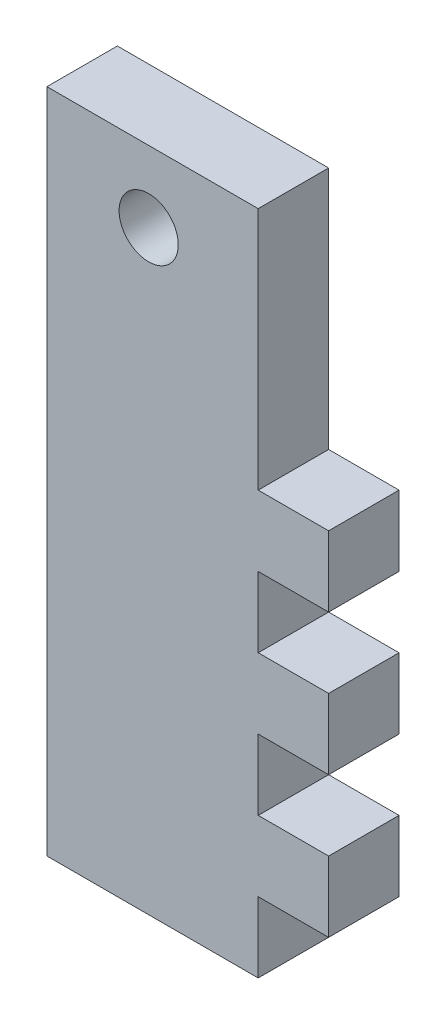
SolidWorks part; units mm, degrees
ref_plane "Plan de face" through (0, 0, 0) normal (0, 0, 1) x (1, 0, 0)
ref_plane "Plan de dessus" through (0, 0, 0) normal (0, 1, 0) x (1, 0, 0)
ref_plane "Plan de droite" through (0, 0, 0) normal (1, 0, 0) x (0, 0, -1)
sketch "Esquisse1" plane through (0, 0, 0) normal (0, 0, 1) x (1, 0, 0)
  line L0 (12.5531, 2.3736) -> (12.5531, 7.9291)
  line L1 (12.5531, 7.9291) -> (12.5531, 19.6836)
  line L2 (12.5531, 19.6836) -> (-2.4469, 19.6836)
  line L5 (-2.4469, -27.6264) -> (12.5531, -27.6264)
  line L6 (12.5531, -27.6264) -> (12.5531, -22.6264)
  line L7 (17.5531, -22.6264) -> (12.5531, -22.6264)
  line L8 (17.5531, -22.6264) -> (17.5531, -17.6264)
  line L9 (17.5531, -17.6264) -> (12.5531, -17.6264)
  line L10 (12.5531, -17.6264) -> (12.5531, -12.6264)
  line L11 (17.5531, -12.6264) -> (12.5531, -12.6264)
  line L12 (17.5531, -12.6264) -> (17.5531, -7.6264)
  line L13 (17.5531, -7.6264) -> (12.5531, -7.6264)
  line L14 (12.5531, -7.6264) -> (12.5531, -2.6264)
  line L15 (17.5531, -2.6264) -> (12.5531, -2.6264)
  line L16 (17.5531, -2.6264) -> (17.5531, 2.3736)
  line L17 (17.5531, 2.3736) -> (12.5531, 2.3736)
  line L18 (-2.4469, 19.6836) -> (-2.4469, -27.6264)
  circle A0 centre (4.7753, 14.6208) radius 2.1
  dimension "D6" = 4.2
  dimension "D1" = 5
  dimension "D2" = 17.31
  dimension "D3" = 5
  dimension "D4" = 15
  dimension "D5" = 15
extrude "Boss.-Extru.1" add sketch "Esquisse1" along normal blind 5
